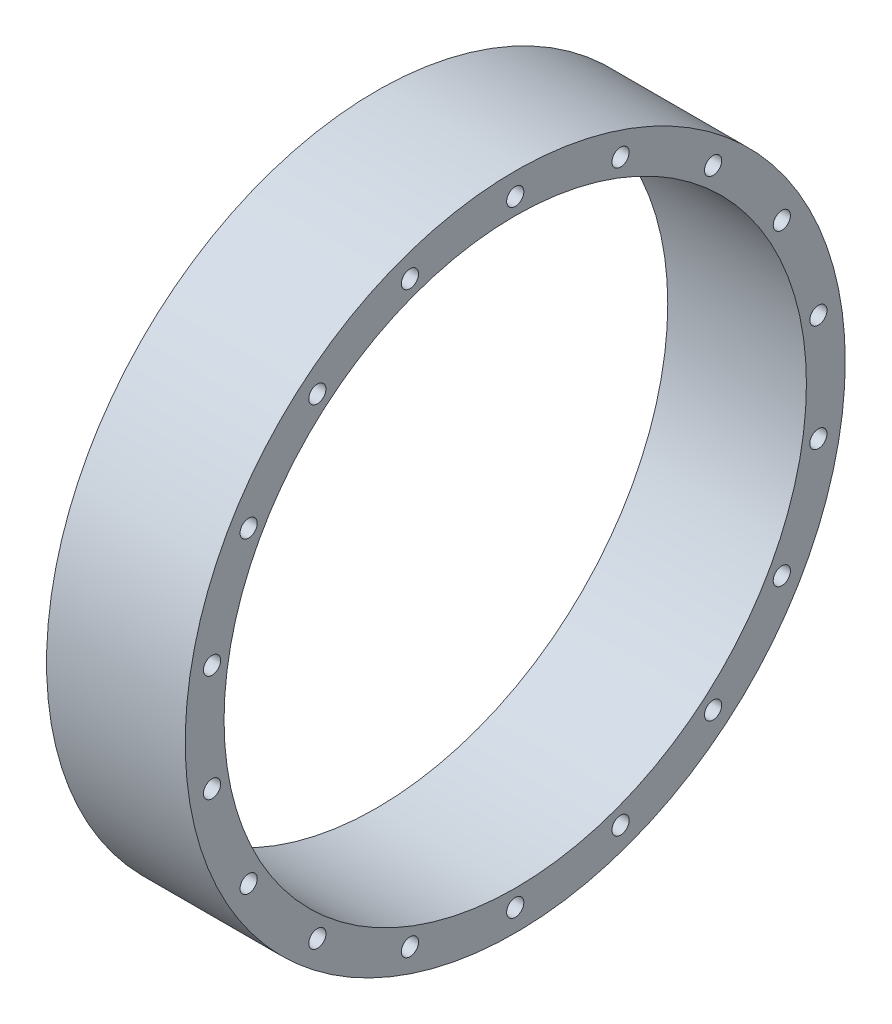
SolidWorks part; units mm, degrees
ref_plane "前视基准面" through (0, 0, 0) normal (0, 0, 1) x (1, 0, 0)
ref_plane "上视基准面" through (0, 0, 0) normal (0, 1, 0) x (1, 0, 0)
ref_plane "右视基准面" through (0, 0, 0) normal (1, 0, 0) x (0, 0, -1)
other "Configuration Table"
sketch "草图1" plane through (0, 0, 0) normal (1, 0, 0) x (0, 0, -1)
  circle A0 centre (0, 0) radius 52.5
  circle A1 centre (0, 0) radius 59.5
  dimension "D1" = 119
  dimension "D2" = 105
extrude "凸台-拉伸1" add sketch "草图1" along normal blind 25
sketch "草图2" plane through (25, 0, 0) normal (1, 0, 0) x (0, 0, -1)
  circle A0 centre (0, 55.5) radius 1.55
  dimension "D2" = 3.1
  dimension "D1" = 55.5
extrude "切除-拉伸1" cut sketch "草图2" against normal through all
pattern_circular "阵列(圆周)1" count 18 every 20 about axis through (0, 0, 0) along (1, 0, 0) of "切除-拉伸1"
